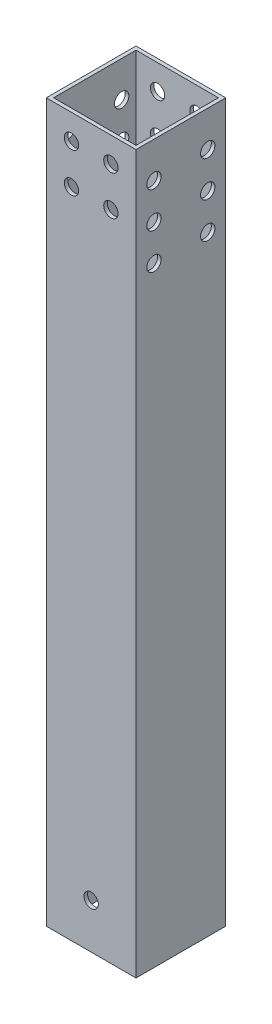
SolidWorks part; units mm, degrees
material "1060 Alloy"
ref_plane "Front Plane" through (0, 0, 0) normal (0, 0, 1) x (1, 0, 0)
ref_plane "Top Plane" through (0, 0, 0) normal (0, 1, 0) x (1, 0, 0)
ref_plane "Right Plane" through (0, 0, 0) normal (1, 0, 0) x (0, 0, -1)
sketch "Sketch1" plane through (0, 0, 0) normal (0, 1, 0) x (1, 0, 0)
  line L0 (-11.5, -11.5) -> (11.5, -11.5)
  line L1 (-12.5, 12.5) -> (12.5, 12.5)
  line L2 (-12.5, 12.5) -> (-12.5, -12.5)
  line L3 (-12.5, -12.5) -> (12.5, -12.5)
  line L4 (12.5, 12.5) -> (12.5, -12.5)
  line L5 (-12.5, 12.5) -> (12.5, -12.5) construction
  line L6 (-12.5, -12.5) -> (12.5, 12.5) construction
  line L7 (11.5, 11.5) -> (11.5, -11.5)
  line L8 (-11.5, 11.5) -> (11.5, 11.5)
  line L9 (-11.5, 11.5) -> (-11.5, -11.5)
  point P0 (0, 0)
  dimension "D1" = 25
  dimension "D2" = 25
  dimension "D3" = 1
extrude "Boss-Extrude1" add sketch "Sketch1" along normal blind 200
sketch "Sketch3" plane through (12.5, 0, 0) normal (1, 0, 0) x (0, 0, -1)
  line L0 (0, 0) -> (0, 288.1425) construction
  line L1 (-12.5, 200) -> (12.5, 200) construction
  circle A0 centre (7.5, 190) radius 2
  circle A1 centre (7.5, 180) radius 2
  circle A3 centre (-7.5, 190) radius 2
  circle A5 centre (-7.5, 180) radius 2
  circle A6 centre (7.5, 170) radius 2
  circle A7 centre (-7.5, 170) radius 2
  dimension "D1" = 7.5
  dimension "D5" = 10
  dimension "D11" = 7.5
  dimension "D2" = 7.5
  dimension "D3" = 7.5
  dimension "D4" = 7.5
  dimension "D6" = 7.5
  dimension "D7" = 10
  dimension "D8" = 10
  dimension "D9" = 10
  dimension "D10" = 10
  dimension "D12" = 10
extrude "Cut-Extrude1" cut sketch "Sketch3" against normal blind 25
sketch "Sketch4" plane through (0, 0, 12.5) normal (0, 0, 1) x (1, 0, 0)
  line L0 (-12.5, 200) -> (12.5, 200) construction
  line L1 (12.5, 200) -> (12.5, 0) construction
  circle A0 centre (5.5, 193) radius 2
  circle A1 centre (5.5, 182) radius 2
  dimension "D1" = 7
  dimension "D2" = 7
  dimension "D3" = 18
  dimension "D4" = 7
extrude "Cut-Extrude2" cut sketch "Sketch4" against normal blind 25
sketch "Sketch5" plane through (0, 0, 12.5) normal (0, 0, 1) x (1, 0, 0)
  line L0 (-12.5, 0) -> (12.5, 0) construction
  line L1 (12.5, 200) -> (12.5, 0) construction
  circle A0 centre (0, 12.5) radius 2
  dimension "D1" = 12.5
  dimension "D2" = 12.5
extrude "Cut-Extrude3" cut sketch "Sketch5" against normal blind 25
mirror "Mirror1" about plane through (0, 0, 0) normal (1, 0, 0) of "Cut-Extrude2"
